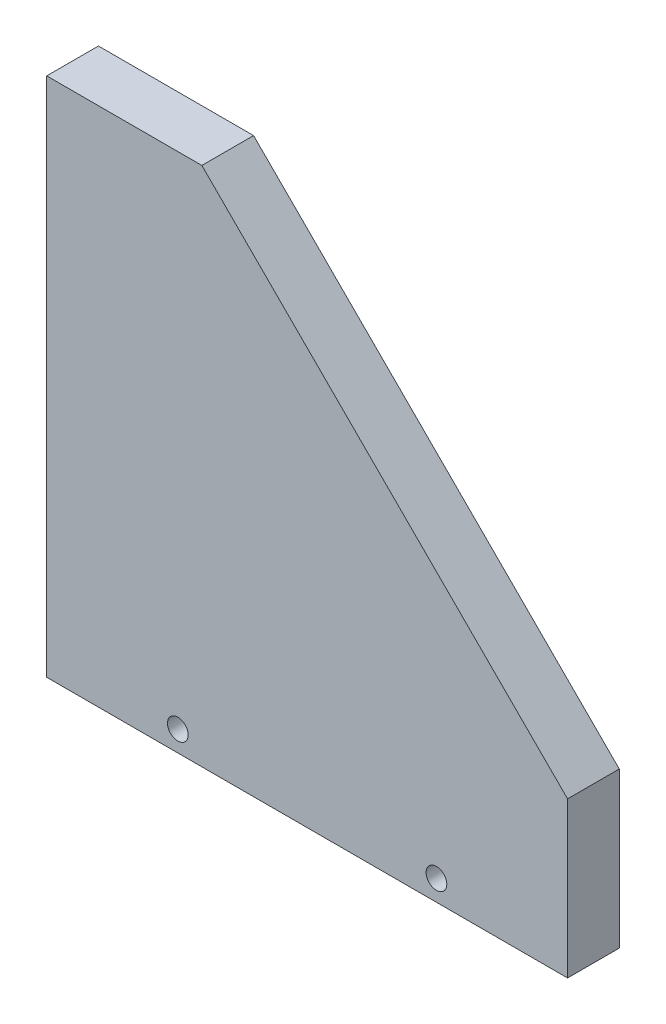
SolidWorks part; units mm, degrees
ref_plane "Plan de face" through (0, 0, 0) normal (0, 0, 1) x (1, 0, 0)
ref_plane "Plan de dessus" through (0, 0, 0) normal (0, 1, 0) x (1, 0, 0)
ref_plane "Plan de droite" through (0, 0, 0) normal (1, 0, 0) x (0, 0, -1)
sketch "Esquisse1" plane through (0, 0, 0) normal (0, 0, 1) x (1, 0, 0)
  line L0 (0, 0) -> (0, 100.7107)
  line L1 (0, 100.7107) -> (30, 100.7107)
  line L2 (30, 100.7107) -> (100.7107, 30)
  line L3 (100.7107, 30) -> (100.7107, 0)
  line L4 (100.7107, 0) -> (0, 0)
  dimension "D1" = 100
  dimension "D2" = 30
  dimension "D3" = 30
  dimension "D4" = 45
extrude "Boss.-Extru.1" add sketch "Esquisse1" along normal blind 10
sketch "Esquisse2" plane through (0, 0, 10) normal (0, 0, 1) x (1, 0, 0)
  line L0 (50.3553, 27.6895) -> (50.3553, 0) construction
  line L1 (0, 0) -> (100.7107, 0) construction
  line L2 (50.3553, 4) -> (25.3553, 4) construction
  circle A0 centre (25.3553, 4) radius 2
  circle A1 centre (75.3553, 4) radius 2
  dimension "D1" = 4
  dimension "D3" = 50
  dimension "D2" = 4
extrude "Enlèv. mat.-Extru.1" cut sketch "Esquisse2" against normal through all both and the other way through all
